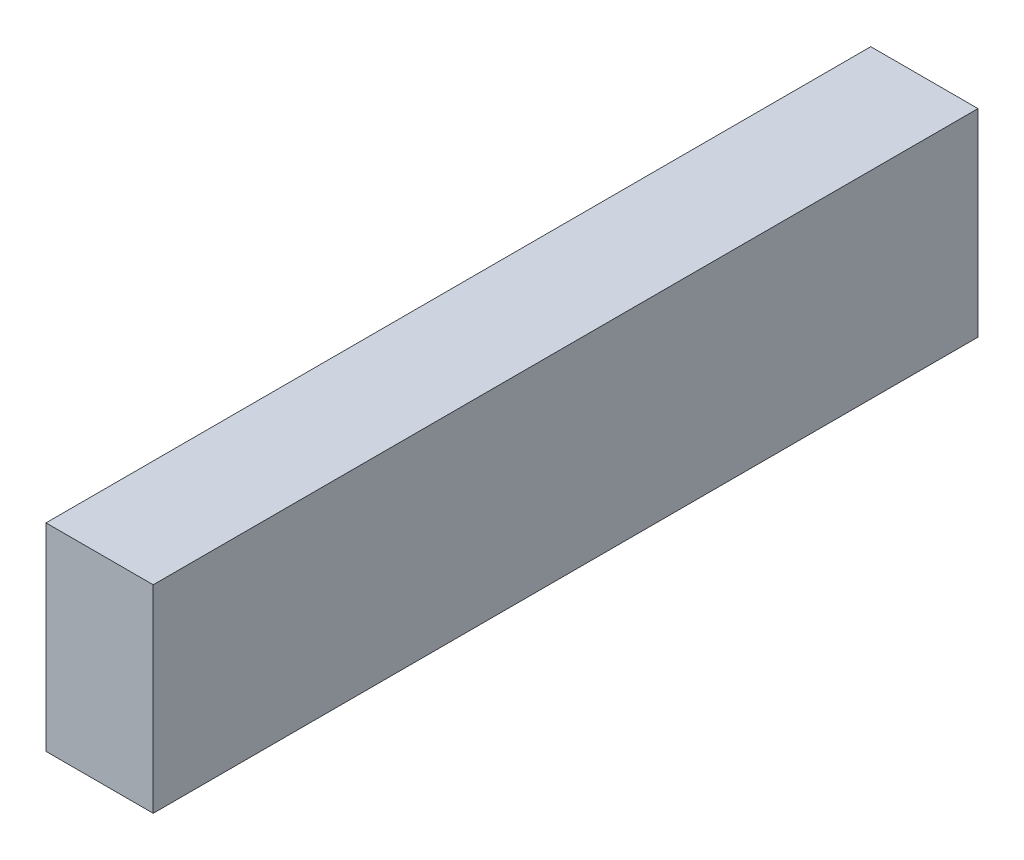
SolidWorks part; units mm, degrees
ref_plane "Front Plane" through (0, 0, 0) normal (0, 0, 1) x (1, 0, 0)
ref_plane "Top Plane" through (0, 0, 0) normal (0, 1, 0) x (1, 0, 0)
ref_plane "Right Plane" through (0, 0, 0) normal (1, 0, 0) x (0, 0, -1)
sketch "草圖1" plane through (0, 0, 0) normal (0, 0, 1) x (1, 0, 0)
  line L0 (-6.5, -12) -> (6.5, -12)
  line L1 (6.5, -12) -> (6.5, 12)
  line L2 (6.5, 12) -> (-6.5, 12)
  line L3 (-6.5, 12) -> (-6.5, -12)
extrude "填料-伸長1" add sketch "草圖1" along normal blind 100
